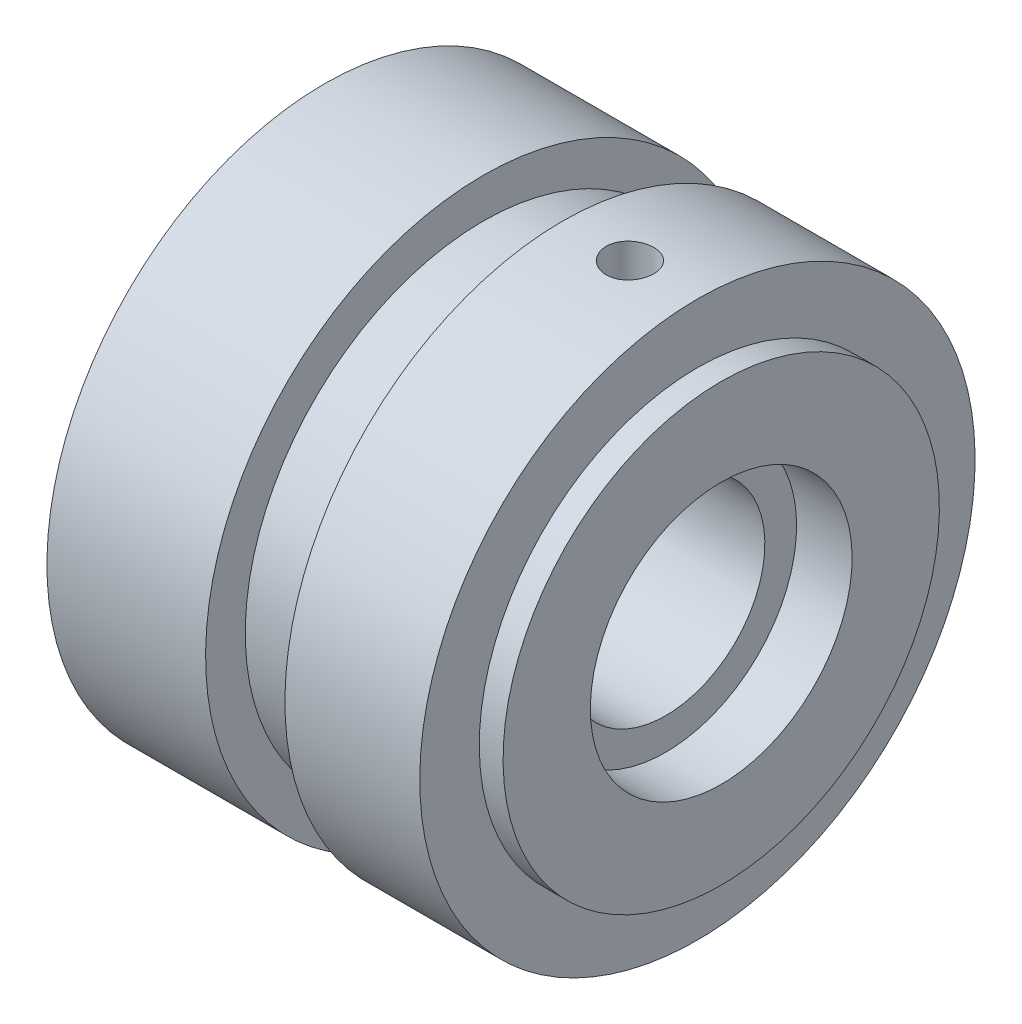
SolidWorks part; units mm, degrees
ref_plane "Front Plane" through (0, 0, 0) normal (0, 0, 1) x (1, 0, 0)
ref_plane "Top Plane" through (0, 0, 0) normal (0, 1, 0) x (1, 0, 0)
ref_plane "Right Plane" through (0, 0, 0) normal (1, 0, 0) x (0, 0, -1)
sketch "Sketch1" plane through (0, 0, 0) normal (0, 0, 1) x (1, 0, 0)
  line L0 (0, 0) -> (0, 30)
  line L2 (5, 35) -> (25, 35)
  line L3 (25, 35) -> (25, 0)
  line L4 (25, 0) -> (0, 0)
  line L5 (25, 12.5) -> (0, 12.5)
  line L9 (5, 35) -> (5, 30)
  line L10 (5, 30) -> (0, 30)
  dimension "D1" = 25
  dimension "D2" = 35
  dimension "D3" = 30
  dimension "D4" = 12.5
  dimension "D8" = 5
revolve "Revolve1" add sketch "Sketch1" angle 360 about L4
mirror "Mirror1" about plane through (0, 0, 0) normal (1, 0, 0) of bodies 101
sketch "Sketch2" plane through (25, 0, 0) normal (1, 0, 0) x (0, 0, -1)
  circle A0 centre (0, 0) radius 12.5
  circle A1 centre (0, 0) radius 16.5
  dimension "D1" = 33
  dimension "D2" = 25
extrude "Cut-Extrude1" cut sketch "Sketch2" against normal blind 7
sketch "Sketch3" plane through (25, 0, 0) normal (1, 0, 0) x (0, 0, -1)
  circle A0 centre (0, 0) radius 35
  circle A1 centre (0, 0) radius 27.5
  dimension "D1" = 55
  dimension "D2" = 70
extrude "Cut-Extrude2" cut sketch "Sketch3" against normal blind 3
ref_plane "Plane1" through (0, 35, 0) normal (0, 1, 0) x (1, 0, 0)
sketch "Sketch4" plane through (0, 35, 0) normal (0, 1, 0) x (1, 0, 0)
  line L0 (22, -35) -> (22, 35) construction
  line L1 (22, 35) -> (5, 35) construction
  circle A0 centre (13.5, 0) radius 3
  dimension "D1" = 6
  dimension "D2" = 8.5
  dimension "D3" = 35
extrude "Cut-Extrude4" cut sketch "Sketch4" against normal blind 25
